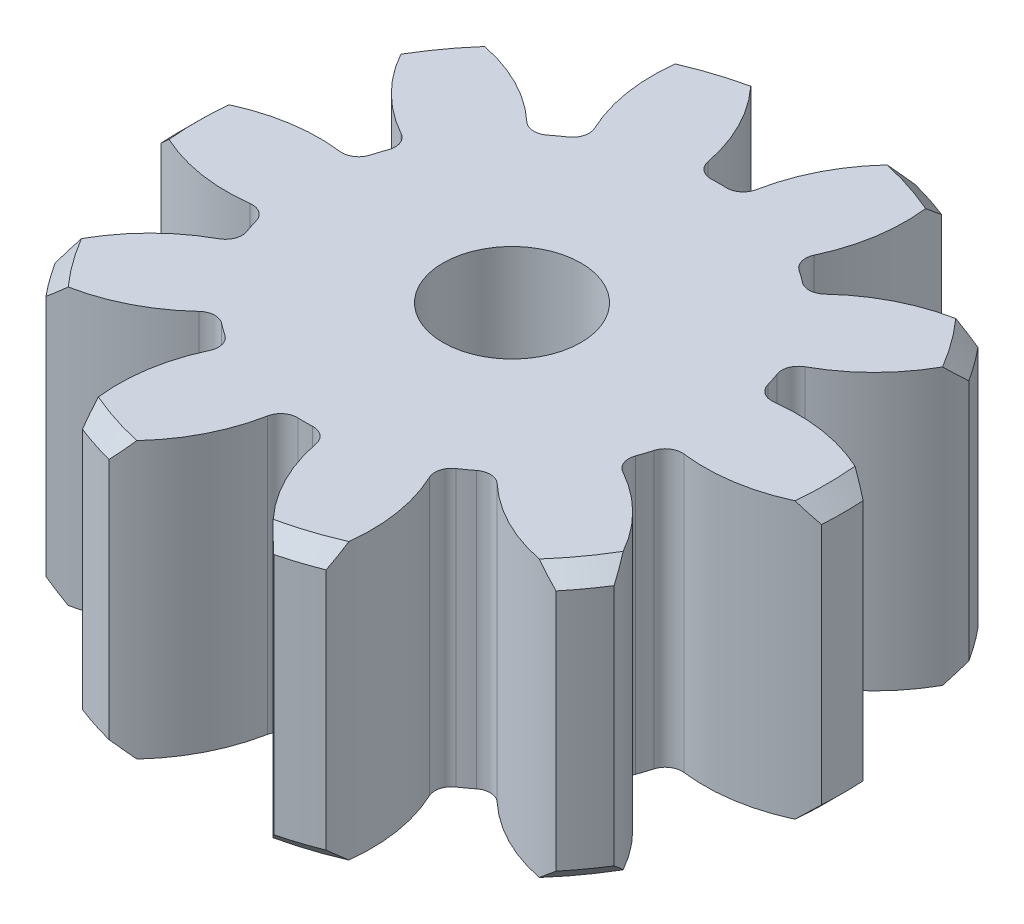
SolidWorks part; units mm, degrees
ref_plane "Front Plane" through (0, 0, 0) normal (0, 0, 1) x (1, 0, 0)
ref_plane "Top Plane" through (0, 0, 0) normal (0, 1, 0) x (1, 0, 0)
ref_plane "Right Plane" through (0, 0, 0) normal (1, 0, 0) x (0, 0, -1)
sketch "Sketch1" plane through (0, 0, 0) normal (0, 1, 0) x (1, 0, 0)
  circle A0 centre (0, 0) radius 10
  circle A1 centre (0, 0) radius 12
  circle A2 centre (0, 0) radius 7.5
  dimension "D1" = 20
  dimension "addendum" = 2
  dimension "dedendum" = 2.5
extrude "Boss-Extrude1" add sketch "Sketch1" along normal blind 10 contours A1
sketch "Sketch2" plane through (0, 0, 0) normal (0, -1, 0) x (1, 0, 0)
  line L0 (0, 0) -> (0, 41.9432) construction
  line L1 (-0.7988, 7.4573) -> (0, 0) construction
  line L2 (0.7988, 7.4573) -> (0, 0) construction
  line L3 (-1.5643, 9.8769) -> (1.5643, 9.8769) construction
  line L4 (-9.948, 25.0013) -> (-8.7995, 22.9295) construction
  line L5 (-1.5643, 9.8769) -> (8.0894, 15.228) construction
  line L6 (-1.5643, 9.8769) -> (2.8642, 10.5783) construction
  line L7 (0, 0) -> (12.8506, 39.5501) construction
  line L8 (1.5643, 9.8769) -> (4.5399, 8.9101) construction
  arc A0 (-2.985, 11.6228) -> (-0.7988, 7.4573) centre (-7.1583, 6.7761) cw
  circle A1 centre (0, 0) radius 12 construction
  circle A2 centre (0, 0) radius 7.5 construction
  arc A3 (2.985, 11.6228) -> (0.7988, 7.4573) centre (7.1583, 6.7761) ccw
  circle A4 centre (0, 0) radius 10 construction
  arc A5 (0.7988, 7.4573) -> (-0.7988, 7.4573) centre (0, 0) ccw
  arc A6 (2.985, 11.6228) -> (-2.985, 11.6228) centre (0, 0) ccw
  point P13 (-1.5643, 9.8769)
  point P14 (1.5643, 9.8769)
  dimension "D1" = 20
  dimension "D2" = 18
extrude "Cut-Extrude1" cut sketch "Sketch2" against normal up to surface (10 mm away) up to face at (0, 10, 12)
fillet "Fillet1" radius 0.6 2 edges at (0.7988, 5, 7.4573) (-0.7988, 5, 7.4573)
chamfer "Chamfer1" distance 0.6 angle 45 2 edges at (0, 0, -12) (0, 10, -12)
pattern_circular "CirPattern1" count 10 over 360 about axis through (0, 0, 0) along (0, 1, 0) of "Cut-Extrude1", "Fillet1"
sketch "Sketch3" plane through (0, 0, 0) normal (0, -1, 0) x (1, 0, 0)
  circle A1 centre (0, 0) radius 2.5
  dimension "D1" = 5
extrude "Cut-Extrude2" cut sketch "Sketch3" against normal up to surface (10 mm away) up to face at (0, 10, 0)
sketch "Sketch4" plane through (0, 0, 0) normal (0, -1, 0) x (1, 0, 0)
  point P0 (0, 0)
equation "\"module\"= 2mm"
equation "\"noTeeth\"= 10"
equation "\"pressureAngle\"= 20deg"
equation "\"width\"= 10mm"
equation "\"D1@Sketch1\"=\"module\"*\"noTeeth\""
equation "\"dedendum@Sketch1\" = \"module\" * 1.25"
equation "\"addendum@Sketch1\" = \"module\""
equation "\"D1@Sketch2\"=\"pressureAngle\""
equation "\"D2@Sketch2\"=180/\"noTeeth\""
equation "\"D1@Fillet1\"=0.3*\"module\""
equation "\"D1@Chamfer1\"=0.3*\"module\""
equation "\"D1@CirPattern1\"=\"noTeeth\""
